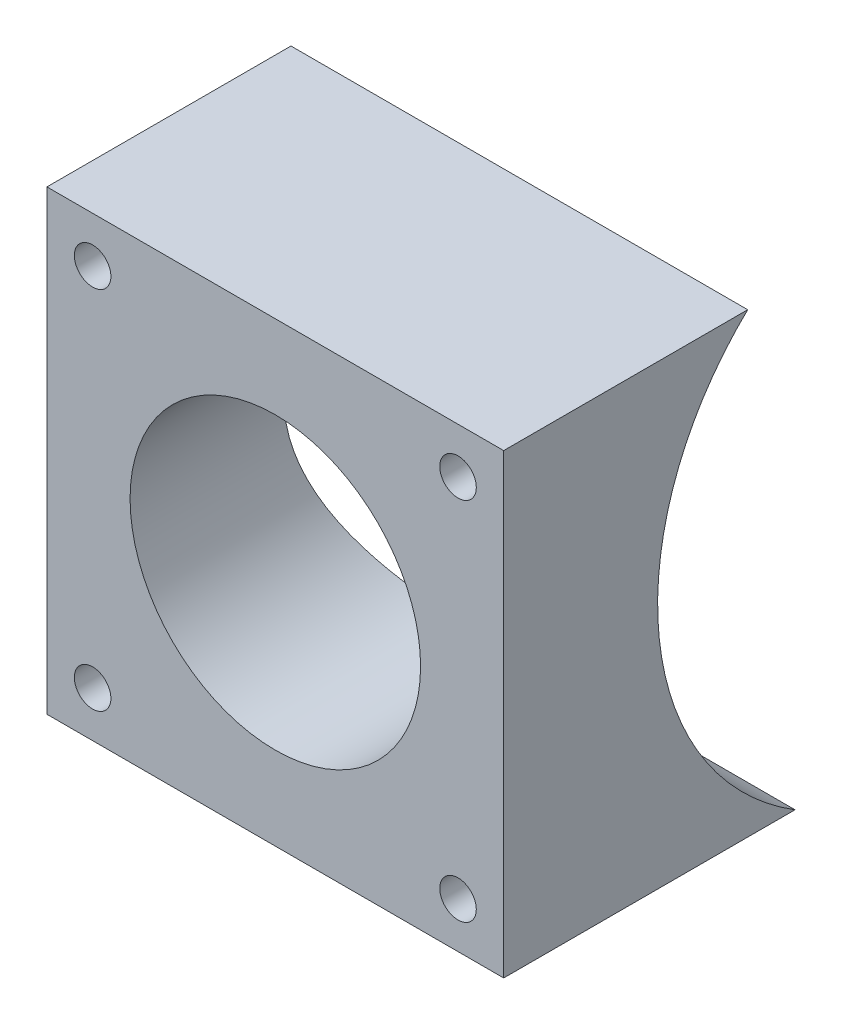
SolidWorks part; units mm, degrees
ref_plane "Front Plane" through (0, 0, 0) normal (0, 0, 1) x (1, 0, 0)
ref_plane "Top Plane" through (0, 0, 0) normal (0, 1, 0) x (1, 0, 0)
ref_plane "Right Plane" through (0, 0, 0) normal (1, 0, 0) x (0, 0, -1)
sketch "Sketch1" plane through (0, 0, 0) normal (0, 0, 1) x (1, 0, 0)
  line L1 (-25, 23) -> (25, 23)
  line L2 (-25, 23) -> (-25, -27)
  line L3 (-25, -27) -> (25, -27)
  line L4 (25, 23) -> (25, -27)
  line L5 (-25, 23) -> (25, -27) construction
  line L6 (-25, -27) -> (25, 23) construction
  circle A0 centre (0, -2) radius 15.9
  circle A1 centre (-20, 18) radius 2
  circle A2 centre (20, 18) radius 2
  circle A3 centre (20, -22) radius 2
  circle A4 centre (-20, -22) radius 2
  point P0 (0, -2)
  dimension "D4" = 31.8
  dimension "D6" = 4
  dimension "D8" = 4
  dimension "D11" = 4
  dimension "D12" = 4
  dimension "D1" = 2
  dimension "D2" = 50
  dimension "D3" = 50
  dimension "D5" = 20
  dimension "D7" = 20
  dimension "D9" = 20
  dimension "D10" = 20
extrude "Boss-Extrude1" add sketch "Sketch1" along normal blind 48.6
sketch "Sketch2" plane through (0, 0, 0) normal (1, 0, 0) x (0, 0, -1)
  circle A0 centre (0, 0) radius 31.75
  dimension "D1" = 63.5
extrude "Cut-Extrude1" cut sketch "Sketch2" against normal through all and the other way through all
